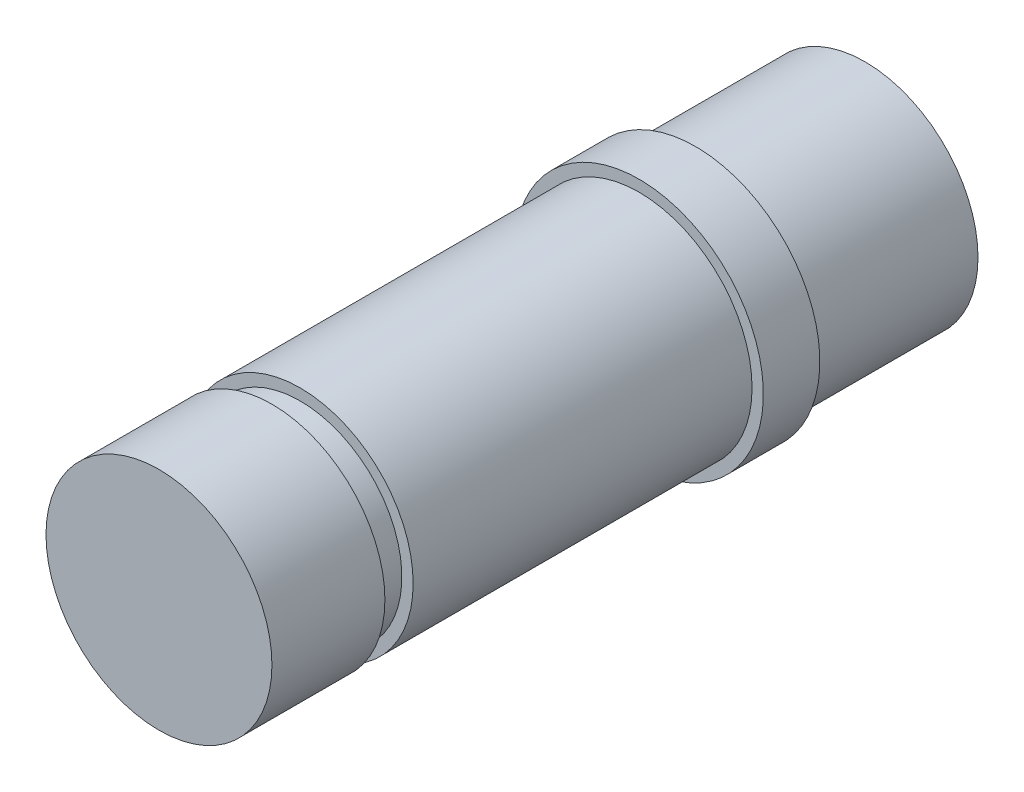
SolidWorks part; units mm, degrees
ref_plane "前视基准面" through (0, 0, 0) normal (0, 0, 1) x (1, 0, 0)
ref_plane "上视基准面" through (0, 0, 0) normal (0, 1, 0) x (1, 0, 0)
ref_plane "右视基准面" through (0, 0, 0) normal (1, 0, 0) x (0, 0, -1)
sketch "草图1" plane through (0, 0, 0) normal (0, 0, 1) x (1, 0, 0)
  circle A0 centre (0, 0) radius 20
  dimension "D1" = 40
extrude "凸台-拉伸1" add sketch "草图1" along normal blind 20
sketch "草图2" plane through (0, 0, 0) normal (0, 0, -1) x (-1, 0, 0)
  circle A0 centre (0, 0) radius 18
extrude "凸台-拉伸2" add sketch "草图2" along normal blind 5
sketch "草图3" plane through (0, 0, -5) normal (0, 0, -1) x (-1, 0, 0)
  circle A0 centre (0, 0) radius 20
extrude "凸台-拉伸3" add sketch "草图3" along normal blind 60
sketch "草图4" plane through (0, 0, -65) normal (0, 0, -1) x (-1, 0, 0)
  circle A0 centre (0, 0) radius 22
extrude "凸台-拉伸4" add sketch "草图4" along normal blind 10
sketch "草图5" plane through (0, 0, -75) normal (0, 0, -1) x (-1, 0, 0)
  circle A0 centre (0, 0) radius 20
extrude "凸台-拉伸5" add sketch "草图5" along normal blind 30
